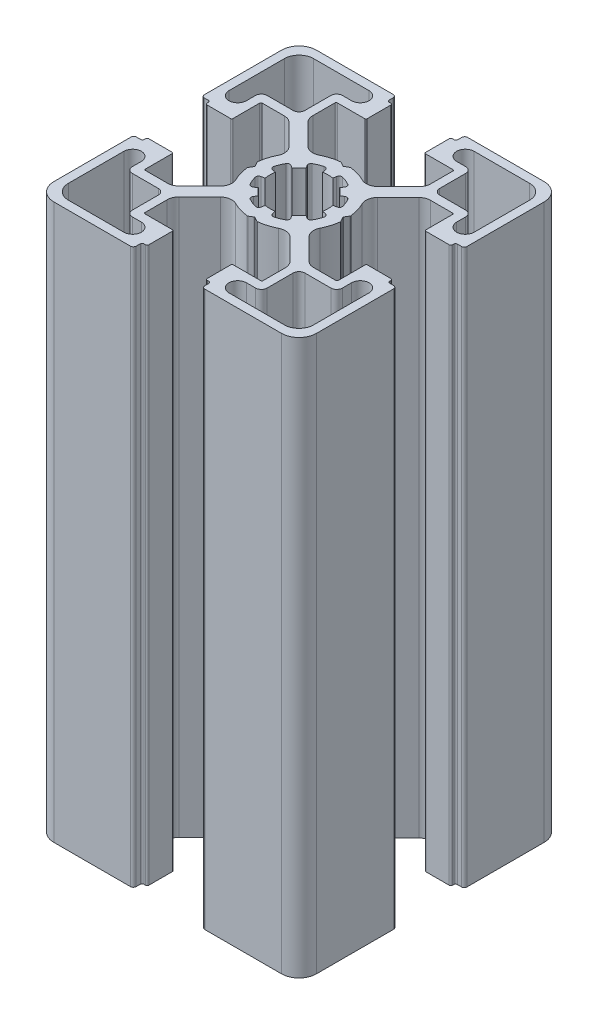
SolidWorks part; units mm, degrees
ref_plane "Front Plane" through (0, 0, 0) normal (0, 0, 1) x (1, 0, 0)
ref_plane "Top Plane" through (0, 0, 0) normal (0, 1, 0) x (1, 0, 0)
ref_plane "Right Plane" through (0, 0, 0) normal (1, 0, 0) x (0, 0, -1)
sketch "Sketch1" plane through (0, 0, 0) normal (0, 1, 0) x (1, 0, 0)
  line L106 (-18, 9.0002) -> (-18, 10.55)
  line L107 (-21, 18.5) -> (-21, 9.0002)
  line L108 (-9, 21) -> (-18.5, 21)
  line L109 (-10.55, 18) -> (-9, 18)
  line L110 (0.9675, 5.4811) -> (0.8674, 4.9242)
  line L111 (2.864, 4.0985) -> (3.1913, 4.5626)
  line L112 (4.5668, 3.2081) -> (4.0897, 2.8765)
  line L113 (4.9205, 0.8878) -> (5.4897, 0.9862)
  line L114 (5.4898, -0.9862) -> (4.9205, -0.8878)
  line L115 (4.0897, -2.8765) -> (4.5668, -3.2082)
  line L116 (3.1914, -4.5627) -> (2.864, -4.0985)
  line L117 (0.8674, -4.9242) -> (0.9675, -5.4811)
  line L118 (-0.9675, -5.4811) -> (-0.8674, -4.9242)
  line L119 (-2.864, -4.0985) -> (-3.1913, -4.5626)
  line L120 (-4.5668, -3.2082) -> (-4.0897, -2.8765)
  line L121 (-4.9205, -0.8878) -> (-5.4897, -0.9862)
  line L122 (-5.4899, 0.9862) -> (-4.9205, 0.8878)
  line L123 (-4.0897, 2.8765) -> (-4.5668, 3.2081)
  line L124 (-3.1914, 4.5627) -> (-2.864, 4.0985)
  line L125 (-0.8674, 4.9242) -> (-0.9675, 5.4811)
  line L126 (-11.55, 12.55) -> (-11.55, 17)
  line L127 (-17, 11.55) -> (-12.55, 11.55)
  line L128 (-21, -9.0002) -> (-21, -18.5)
  line L129 (-18, -10.55) -> (-18, -9.0002)
  line L130 (-12.55, -11.55) -> (-17, -11.55)
  line L131 (-11.55, -17) -> (-11.55, -12.55)
  line L132 (-9, -18) -> (-10.55, -18)
  line L133 (-18.5, -21) -> (-9, -21)
  line L134 (21, 9.0002) -> (21, 18.5)
  line L135 (18, 10.55) -> (18, 9.0002)
  line L136 (12.55, 11.55) -> (17, 11.55)
  line L137 (11.55, 17) -> (11.55, 12.55)
  line L138 (9, 18) -> (10.55, 18)
  line L139 (18.5, 21) -> (9, 21)
  line L140 (17, -11.55) -> (12.55, -11.55)
  line L141 (18, -9.0002) -> (18, -10.55)
  line L142 (21, -18.5) -> (21, -9.0002)
  line L143 (9, -21) -> (18.5, -21)
  line L144 (10.55, -18) -> (9, -18)
  line L145 (11.55, -12.55) -> (11.55, -17)
  line L146 (7.5635, 5.8587) -> (11.1298, 9.425)
  line L147 (12.5048, 9.9945) -> (16.3169, 9.9945)
  line L148 (16.5169, 9.7945) -> (16.5169, 5.2)
  line L149 (16.7169, 5) -> (20.7196, 5)
  line L150 (21.0196, 5.3) -> (21.0196, 5.5)
  line L151 (21.3196, 5.8) -> (22, 5.8)
  line L152 (22.5, 6.3) -> (22.5, 19.5)
  line L153 (19.5, 22.5) -> (6.3757, 22.5)
  line L154 (5.8757, 22) -> (5.8757, 21.3)
  line L155 (5.5757, 21) -> (5.3, 21)
  line L156 (5, 20.7) -> (5, 16.6668)
  line L157 (5.2, 16.4668) -> (9.9054, 16.4668)
  line L158 (10.1054, 16.2668) -> (10.1054, 12.4716)
  line L159 (9.5196, 11.0574) -> (5.9449, 7.4827)
  line L160 (0.7548, 7.9748) -> (0.1126, 7.6069)
  line L161 (-0.1126, 7.6069) -> (-0.7547, 7.9748)
  line L162 (-5.9449, 7.4827) -> (-9.5196, 11.0574)
  line L163 (-10.1054, 12.4716) -> (-10.1054, 16.2668)
  line L164 (-9.9054, 16.4668) -> (-5.2, 16.4668)
  line L165 (-5, 16.6668) -> (-5, 20.7)
  line L166 (-5.3, 21) -> (-5.5757, 21)
  line L167 (-5.8757, 21.3) -> (-5.8757, 22)
  line L168 (-6.3757, 22.5) -> (-19.5, 22.5)
  line L169 (-22.5, 19.5) -> (-22.5, 6.3)
  line L170 (-22, 5.8) -> (-21.3196, 5.8)
  line L171 (-21.0196, 5.5) -> (-21.0196, 5.3)
  line L172 (-20.7196, 5) -> (-16.7169, 5)
  line L173 (-16.5169, 5.2) -> (-16.5169, 9.7945)
  line L174 (-16.3169, 9.9945) -> (-12.5048, 9.9945)
  line L175 (-11.1298, 9.425) -> (-7.5635, 5.8587)
  line L176 (-7.974, 0.7926) -> (-7.5401, 0.0468)
  line L177 (-7.5401, -0.0468) -> (-7.974, -0.7926)
  line L178 (-7.5635, -5.8587) -> (-11.1298, -9.425)
  line L179 (-12.5048, -9.9945) -> (-16.3169, -9.9945)
  line L180 (-16.5169, -9.7945) -> (-16.5169, -5.2)
  line L181 (-16.7169, -5) -> (-20.7196, -5)
  line L182 (-21.0196, -5.3) -> (-21.0196, -5.5)
  line L183 (-21.3196, -5.8) -> (-22, -5.8)
  line L184 (-22.5, -6.3) -> (-22.5, -19.5)
  line L185 (-19.5, -22.5) -> (-6.3757, -22.5)
  line L186 (-5.8757, -22) -> (-5.8757, -21.3)
  line L187 (-5.5757, -21) -> (-5.3, -21)
  line L188 (-5, -20.7) -> (-5, -16.6668)
  line L189 (-5.2, -16.4668) -> (-9.9054, -16.4668)
  line L190 (-10.1054, -16.2668) -> (-10.1054, -12.4716)
  line L191 (-9.5196, -11.0574) -> (-5.9449, -7.4827)
  line L192 (-0.7547, -7.9748) -> (-0.1126, -7.6069)
  line L193 (0.1126, -7.6069) -> (0.7548, -7.9748)
  line L194 (5.9449, -7.4827) -> (9.5196, -11.0574)
  line L195 (10.1054, -12.4716) -> (10.1054, -16.2668)
  line L196 (9.9054, -16.4668) -> (5.2, -16.4668)
  line L197 (5, -16.6668) -> (5, -20.7)
  line L198 (5.3, -21) -> (5.5757, -21)
  line L199 (5.8757, -21.3) -> (5.8757, -22)
  line L200 (6.3757, -22.5) -> (19.5, -22.5)
  line L201 (22.5, -19.5) -> (22.5, -6.3)
  line L202 (22, -5.8) -> (21.3196, -5.8)
  line L203 (21.0196, -5.5) -> (21.0196, -5.3)
  line L204 (20.7196, -5) -> (16.7169, -5)
  line L205 (16.5169, -5.2) -> (16.5169, -9.7945)
  line L206 (16.3169, -9.9945) -> (12.5048, -9.9945)
  line L207 (11.1298, -9.425) -> (7.5635, -5.8587)
  line L208 (7.974, -0.7926) -> (7.5401, -0.0468)
  line L209 (7.5401, 0.0468) -> (7.974, 0.7926)
  arc A140 (-17, 11.55) -> (-18, 10.55) centre (-17, 10.55) ccw
  arc A141 (-21, 9.0002) -> (-18, 9.0002) centre (-19.5, 9.0002) ccw
  arc A142 (-18.5, 21) -> (-21, 18.5) centre (-18.5, 18.5) ccw
  arc A143 (-9, 18) -> (-9, 21) centre (-9, 19.5) ccw
  arc A144 (-10.55, 18) -> (-11.55, 17) centre (-10.55, 17) ccw
  arc A145 (-12.55, 11.55) -> (-11.55, 12.55) centre (-12.55, 12.55) ccw
  arc A146 (-21, -18.5) -> (-18.5, -21) centre (-18.5, -18.5) ccw
  arc A147 (-18, -9.0002) -> (-21, -9.0002) centre (-19.5, -9.0002) ccw
  arc A148 (-18, -10.55) -> (-17, -11.55) centre (-17, -10.55) ccw
  arc A149 (-11.55, -12.55) -> (-12.55, -11.55) centre (-12.55, -12.55) ccw
  arc A150 (-11.55, -17) -> (-10.55, -18) centre (-10.55, -17) ccw
  arc A151 (-9, -21) -> (-9, -18) centre (-9, -19.5) ccw
  arc A152 (0.8674, 4.9242) -> (-0.8674, 4.9242) centre (0, 0) ccw
  arc A153 (1.5951, 5.8941) -> (0.9675, 5.4811) centre (1.4627, 5.4119) ccw
  arc A154 (3.0417, 5.301) -> (1.5951, 5.8941) centre (0.0235, 0) ccw
  arc A155 (3.1913, 4.5626) -> (3.0417, 5.301) centre (2.7943, 4.8665) ccw
  arc A156 (4.0897, 2.8765) -> (2.864, 4.0985) centre (0, 0) ccw
  arc A157 (5.3025, 3.0565) -> (4.5668, 3.2081) centre (4.868, 2.8091) ccw
  arc A158 (5.906, 1.6142) -> (5.3025, 3.0565) centre (0.0235, 0) ccw
  arc A159 (5.4897, 0.9862) -> (5.906, 1.6142) centre (5.4239, 1.4819) ccw
  arc A160 (4.9205, -0.8878) -> (4.9205, 0.8878) centre (0, 0) ccw
  arc A161 (5.906, -1.6142) -> (5.4898, -0.9862) centre (5.4239, -1.4819) ccw
  arc A162 (5.3025, -3.0564) -> (5.906, -1.6142) centre (0.0235, 0) ccw
  arc A163 (4.5668, -3.2082) -> (5.3025, -3.0564) centre (4.868, -2.8091) ccw
  arc A164 (2.864, -4.0985) -> (4.0897, -2.8765) centre (0, 0) ccw
  arc A165 (3.0416, -5.301) -> (3.1914, -4.5627) centre (2.7943, -4.8665) ccw
  arc A166 (1.5951, -5.8941) -> (3.0416, -5.301) centre (0.0235, 0) ccw
  arc A167 (0.9675, -5.4811) -> (1.5951, -5.8941) centre (1.4627, -5.4119) ccw
  arc A168 (-0.8674, -4.9242) -> (0.8674, -4.9242) centre (0, 0) ccw
  arc A169 (-1.5951, -5.8941) -> (-0.9675, -5.4811) centre (-1.4627, -5.4119) ccw
  arc A170 (-3.0416, -5.301) -> (-1.5951, -5.8941) centre (-0.0235, 0) ccw
  arc A171 (-3.1913, -4.5626) -> (-3.0416, -5.301) centre (-2.7943, -4.8665) ccw
  arc A172 (-4.0897, -2.8765) -> (-2.864, -4.0985) centre (0, 0) ccw
  arc A173 (-5.3025, -3.0565) -> (-4.5668, -3.2082) centre (-4.868, -2.8091) ccw
  arc A174 (-5.906, -1.6142) -> (-5.3025, -3.0565) centre (-0.0235, 0) ccw
  arc A175 (-5.4897, -0.9862) -> (-5.906, -1.6142) centre (-5.4239, -1.4819) ccw
  arc A176 (-4.9205, 0.8878) -> (-4.9205, -0.8878) centre (0, 0) ccw
  arc A177 (-5.906, 1.6141) -> (-5.4899, 0.9862) centre (-5.4239, 1.4818) ccw
  arc A178 (-5.3025, 3.0564) -> (-5.906, 1.6141) centre (-0.0235, 0) ccw
  arc A179 (-4.5668, 3.2081) -> (-5.3025, 3.0564) centre (-4.868, 2.8091) ccw
  arc A180 (-2.864, 4.0985) -> (-4.0897, 2.8765) centre (0, 0) ccw
  arc A181 (-3.0417, 5.301) -> (-3.1914, 4.5627) centre (-2.7943, 4.8665) ccw
  arc A182 (-1.5951, 5.8941) -> (-3.0417, 5.301) centre (-0.0235, 0) ccw
  arc A183 (-0.9675, 5.4811) -> (-1.5951, 5.8941) centre (-1.4627, 5.4119) ccw
  arc A184 (21, 18.5) -> (18.5, 21) centre (18.5, 18.5) ccw
  arc A185 (18, 9.0002) -> (21, 9.0002) centre (19.5, 9.0002) ccw
  arc A186 (18, 10.55) -> (17, 11.55) centre (17, 10.55) ccw
  arc A187 (11.55, 12.55) -> (12.55, 11.55) centre (12.55, 12.55) ccw
  arc A188 (11.55, 17) -> (10.55, 18) centre (10.55, 17) ccw
  arc A189 (9, 21) -> (9, 18) centre (9, 19.5) ccw
  arc A190 (12.55, -11.55) -> (11.55, -12.55) centre (12.55, -12.55) ccw
  arc A191 (17, -11.55) -> (18, -10.55) centre (17, -10.55) ccw
  arc A192 (21, -9.0002) -> (18, -9.0002) centre (19.5, -9.0002) ccw
  arc A193 (18.5, -21) -> (21, -18.5) centre (18.5, -18.5) ccw
  arc A194 (9, -18) -> (9, -21) centre (9, -19.5) ccw
  arc A195 (10.55, -18) -> (11.55, -17) centre (10.55, -17) ccw
  arc A196 (7.9999, 0.9154) -> (7.2004, 3.6119) centre (0.0496, 0.0249) ccw
  arc A197 (7.5635, 5.8587) -> (7.2004, 3.6119) centre (8.9385, 4.4837) ccw
  arc A198 (12.5048, 9.9945) -> (11.1298, 9.425) centre (12.5048, 8.05) ccw
  arc A199 (16.5169, 9.7945) -> (16.3169, 9.9945) centre (16.3169, 9.7945) ccw
  arc A200 (16.5169, 5.2) -> (16.7169, 5) centre (16.7169, 5.2) ccw
  arc A201 (20.7196, 5) -> (21.0196, 5.3) centre (20.7196, 5.3) ccw
  arc A202 (21.3196, 5.8) -> (21.0196, 5.5) centre (21.3196, 5.5) ccw
  arc A203 (22, 5.8) -> (22.5, 6.3) centre (22, 6.3) ccw
  arc A204 (22.5, 19.5) -> (19.5, 22.5) centre (19.5, 19.5) ccw
  arc A205 (6.3757, 22.5) -> (5.8757, 22) centre (6.3757, 22) ccw
  arc A206 (5.5757, 21) -> (5.8757, 21.3) centre (5.5757, 21.3) ccw
  arc A207 (5.3, 21) -> (5, 20.7) centre (5.3, 20.7) ccw
  arc A208 (5, 16.6668) -> (5.2, 16.4668) centre (5.2, 16.6668) ccw
  arc A209 (10.1054, 16.2668) -> (9.9054, 16.4668) centre (9.9054, 16.2668) ccw
  arc A210 (9.5196, 11.0574) -> (10.1054, 12.4716) centre (8.1054, 12.4716) ccw
  arc A211 (3.6665, 7.1733) -> (5.9449, 7.4827) centre (4.5855, 8.9496) ccw
  arc A212 (3.6665, 7.1733) -> (0.8753, 8.0001) centre (0.0235, 0) ccw
  arc A213 (0.8753, 8.0001) -> (0.7548, 7.9748) centre (0.8542, 7.8013) ccw
  arc A214 (0, 7.531) -> (0.1126, 7.6069) centre (-0.0489, 7.7249) ccw
  arc A215 (-0.1126, 7.6069) -> (0, 7.531) centre (0.0489, 7.7249) ccw
  arc A216 (-0.7547, 7.9748) -> (-0.8753, 8.0001) centre (-0.8542, 7.8013) ccw
  arc A217 (-0.8753, 8.0001) -> (-3.6665, 7.1733) centre (-0.0235, 0) ccw
  arc A218 (-5.9449, 7.4827) -> (-3.6665, 7.1733) centre (-4.5855, 8.9496) ccw
  arc A219 (-10.1054, 12.4716) -> (-9.5196, 11.0574) centre (-8.1054, 12.4716) ccw
  arc A220 (-9.9054, 16.4668) -> (-10.1054, 16.2668) centre (-9.9054, 16.2668) ccw
  arc A221 (-5.2, 16.4668) -> (-5, 16.6668) centre (-5.2, 16.6668) ccw
  arc A222 (-5, 20.7) -> (-5.3, 21) centre (-5.3, 20.7) ccw
  arc A223 (-5.8757, 21.3) -> (-5.5757, 21) centre (-5.5757, 21.3) ccw
  arc A224 (-5.8757, 22) -> (-6.3757, 22.5) centre (-6.3757, 22) ccw
  arc A225 (-19.5, 22.5) -> (-22.5, 19.5) centre (-19.5, 19.5) ccw
  arc A226 (-22.5, 6.3) -> (-22, 5.8) centre (-22, 6.3) ccw
  arc A227 (-21.0196, 5.5) -> (-21.3196, 5.8) centre (-21.3196, 5.5) ccw
  arc A228 (-21.0196, 5.3) -> (-20.7196, 5) centre (-20.7196, 5.3) ccw
  arc A229 (-16.7169, 5) -> (-16.5169, 5.2) centre (-16.7169, 5.2) ccw
  arc A230 (-16.3169, 9.9945) -> (-16.5169, 9.7945) centre (-16.3169, 9.7945) ccw
  arc A231 (-11.1298, 9.425) -> (-12.5048, 9.9945) centre (-12.5048, 8.05) ccw
  arc A232 (-7.2004, 3.6119) -> (-7.5635, 5.8587) centre (-8.9385, 4.4837) ccw
  arc A233 (-7.2004, 3.6119) -> (-7.9999, 0.9154) centre (-0.0496, 0.0249) ccw
  arc A234 (-7.9999, 0.9154) -> (-7.974, 0.7926) centre (-7.8011, 0.8932) ccw
  arc A235 (-7.5313, 0) -> (-7.5401, 0.0468) centre (-7.7309, -0.013) ccw
  arc A236 (-7.5401, -0.0468) -> (-7.5313, 0) centre (-7.7309, 0.013) ccw
  arc A237 (-7.974, -0.7926) -> (-7.9999, -0.9154) centre (-7.8011, -0.8932) ccw
  arc A238 (-7.9999, -0.9154) -> (-7.2004, -3.6119) centre (-0.0496, -0.0249) ccw
  arc A239 (-7.5635, -5.8587) -> (-7.2004, -3.6119) centre (-8.9385, -4.4837) ccw
  arc A240 (-12.5048, -9.9945) -> (-11.1298, -9.425) centre (-12.5048, -8.05) ccw
  arc A241 (-16.5169, -9.7945) -> (-16.3169, -9.9945) centre (-16.3169, -9.7945) ccw
  arc A242 (-16.5169, -5.2) -> (-16.7169, -5) centre (-16.7169, -5.2) ccw
  arc A243 (-20.7196, -5) -> (-21.0196, -5.3) centre (-20.7196, -5.3) ccw
  arc A244 (-21.3196, -5.8) -> (-21.0196, -5.5) centre (-21.3196, -5.5) ccw
  arc A245 (-22, -5.8) -> (-22.5, -6.3) centre (-22, -6.3) ccw
  arc A246 (-22.5, -19.5) -> (-19.5, -22.5) centre (-19.5, -19.5) ccw
  arc A247 (-6.3757, -22.5) -> (-5.8757, -22) centre (-6.3757, -22) ccw
  arc A248 (-5.5757, -21) -> (-5.8757, -21.3) centre (-5.5757, -21.3) ccw
  arc A249 (-5.3, -21) -> (-5, -20.7) centre (-5.3, -20.7) ccw
  arc A250 (-5, -16.6668) -> (-5.2, -16.4668) centre (-5.2, -16.6668) ccw
  arc A251 (-10.1054, -16.2668) -> (-9.9054, -16.4668) centre (-9.9054, -16.2668) ccw
  arc A252 (-9.5196, -11.0574) -> (-10.1054, -12.4716) centre (-8.1054, -12.4716) ccw
  arc A253 (-3.6665, -7.1733) -> (-5.9449, -7.4827) centre (-4.5855, -8.9496) ccw
  arc A254 (-3.6665, -7.1733) -> (-0.8753, -8.0001) centre (-0.0235, 0) ccw
  arc A255 (-0.8753, -8.0001) -> (-0.7547, -7.9748) centre (-0.8542, -7.8013) ccw
  arc A256 (0, -7.531) -> (-0.1126, -7.6069) centre (0.0489, -7.7249) ccw
  arc A257 (0.1126, -7.6069) -> (0, -7.531) centre (-0.0489, -7.7249) ccw
  arc A258 (0.7548, -7.9748) -> (0.8753, -8.0001) centre (0.8542, -7.8012) ccw
  arc A259 (0.8753, -8.0001) -> (3.6665, -7.1733) centre (0.0235, 0) ccw
  arc A260 (5.9449, -7.4827) -> (3.6665, -7.1733) centre (4.5855, -8.9496) ccw
  arc A261 (10.1054, -12.4716) -> (9.5196, -11.0574) centre (8.1054, -12.4716) ccw
  arc A262 (9.9054, -16.4668) -> (10.1054, -16.2668) centre (9.9054, -16.2668) ccw
  arc A263 (5.2, -16.4668) -> (5, -16.6668) centre (5.2, -16.6668) ccw
  arc A264 (5, -20.7) -> (5.3, -21) centre (5.3, -20.7) ccw
  arc A265 (5.8757, -21.3) -> (5.5757, -21) centre (5.5757, -21.3) ccw
  arc A266 (5.8757, -22) -> (6.3757, -22.5) centre (6.3757, -22) ccw
  arc A267 (19.5, -22.5) -> (22.5, -19.5) centre (19.5, -19.5) ccw
  arc A268 (22.5, -6.3) -> (22, -5.8) centre (22, -6.3) ccw
  arc A269 (21.0196, -5.5) -> (21.3196, -5.8) centre (21.3196, -5.5) ccw
  arc A270 (21.0196, -5.3) -> (20.7196, -5) centre (20.7196, -5.3) ccw
  arc A271 (16.7169, -5) -> (16.5169, -5.2) centre (16.7169, -5.2) ccw
  arc A272 (16.3169, -9.9945) -> (16.5169, -9.7945) centre (16.3169, -9.7945) ccw
  arc A273 (11.1298, -9.425) -> (12.5048, -9.9945) centre (12.5048, -8.05) ccw
  arc A274 (7.2004, -3.6119) -> (7.5635, -5.8587) centre (8.9385, -4.4837) ccw
  arc A275 (7.2004, -3.6119) -> (7.9999, -0.9154) centre (0.0496, -0.0249) ccw
  arc A276 (7.9999, -0.9154) -> (7.974, -0.7926) centre (7.8011, -0.8932) ccw
  arc A277 (7.5313, 0) -> (7.5401, -0.0468) centre (7.7309, 0.013) ccw
  arc A278 (7.5401, 0.0468) -> (7.5313, 0) centre (7.7309, -0.013) ccw
  arc A279 (7.974, 0.7926) -> (7.9999, 0.9154) centre (7.8011, 0.8932) ccw
extrude "Boss-Extrude1" add sketch "Sketch1" along normal blind 95
